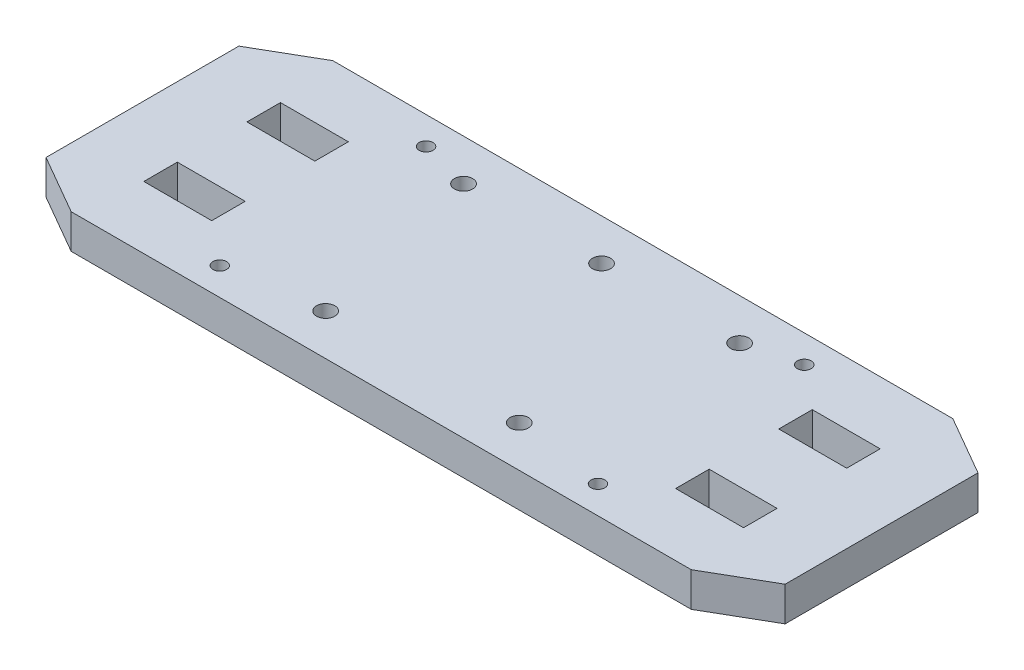
SolidWorks part; units mm, degrees
ref_plane "Front Plane" through (0, 0, 0) normal (0, 0, 1) x (1, 0, 0)
ref_plane "Top Plane" through (0, 0, 0) normal (0, 1, 0) x (1, 0, 0)
ref_plane "Right Plane" through (0, 0, 0) normal (1, 0, 0) x (0, 0, -1)
sketch "Sketch1" plane through (0, 0, 0) normal (0, 1, 0) x (1, 0, 0)
  line L0 (0, 38.05) -> (0, -38.05) construction
  line L1 (48.15, -20.05) -> (-48.15, -20.05) construction
  line L2 (48.15, -20.05) -> (48.15, 20.05) construction
  line L3 (48.15, 20.05) -> (-48.15, 20.05) construction
  line L4 (-48.15, -20.05) -> (-48.15, 20.05) construction
  line L5 (48.15, -20.05) -> (-48.15, 20.05) construction
  line L6 (48.15, 20.05) -> (-48.15, -20.05) construction
  line L7 (107.5, -38.05) -> (-107.5, -38.05)
  line L8 (107.5, -38.05) -> (107.5, 38.05)
  line L9 (107.5, 38.05) -> (-107.5, 38.05)
  line L10 (-107.5, -38.05) -> (-107.5, 38.05)
  line L11 (107.5, -38.05) -> (-107.5, 38.05) construction
  line L12 (107.5, 38.05) -> (-107.5, -38.05) construction
  circle A0 centre (-40.15, 26.05) radius 2.65
  circle A1 centre (40.15, 26.05) radius 2.65
  circle A2 centre (0, 26.05) radius 2.65
  circle A3 centre (-28.15, -26.05) radius 2.65
  circle A4 centre (28.15, -26.05) radius 2.65
  point P0 (0, 0)
  point P6 (0, 0)
  dimension "D3" = 5.3
  dimension "D1" = 96.3
  dimension "D2" = 40.1
  dimension "D4" = 6
  dimension "D5" = 8
  dimension "D6" = 6
  dimension "D7" = 20
  dimension "D8" = 215
  dimension "D9" = 12
extrude "Boss-Extrude1" add sketch "Sketch1" along normal blind 10
sketch "Sketch2" plane through (0, 10, 0) normal (0, 1, 0) x (1, 0, 0)
  line L0 (0, 0) -> (-70.9493, 0) construction
  line L1 (-87.225, -19.875) -> (-67.475, -19.875)
  line L2 (-87.225, -19.875) -> (-87.225, -10.125)
  line L3 (-87.225, -10.125) -> (-67.475, -10.125)
  line L4 (-67.475, -19.875) -> (-67.475, -10.125)
  line L5 (-87.225, -19.875) -> (-67.475, -10.125) construction
  line L6 (-87.225, -10.125) -> (-67.475, -19.875) construction
  line L7 (0, 0) -> (0, -12.151) construction
  line L8 (-87.225, 10.125) -> (-67.475, 19.875) construction
  line L9 (-87.225, 19.875) -> (-67.475, 10.125) construction
  line L10 (-67.475, 19.875) -> (-67.475, 10.125)
  line L11 (-87.225, 10.125) -> (-67.475, 10.125)
  line L12 (-87.225, 19.875) -> (-87.225, 10.125)
  line L13 (-87.225, 19.875) -> (-67.475, 19.875)
  line L14 (87.225, 19.875) -> (67.475, 10.125) construction
  line L15 (87.225, 10.125) -> (67.475, 19.875) construction
  line L16 (87.225, -10.125) -> (67.475, -19.875) construction
  line L17 (87.225, -19.875) -> (67.475, -10.125) construction
  line L18 (87.225, 19.875) -> (67.475, 19.875)
  line L19 (87.225, 19.875) -> (87.225, 10.125)
  line L20 (87.225, 10.125) -> (67.475, 10.125)
  line L21 (67.475, 19.875) -> (67.475, 10.125)
  line L22 (67.475, -19.875) -> (67.475, -10.125)
  line L23 (87.225, -10.125) -> (67.475, -10.125)
  line L24 (87.225, -19.875) -> (87.225, -10.125)
  line L25 (87.225, -19.875) -> (67.475, -19.875)
  point P0 (-77.35, -15)
  point P13 (-77.35, 15)
  point P22 (77.35, 15)
  point P23 (77.35, -15)
  dimension "D1" = 15
  dimension "D2" = 77.35
  dimension "D3" = 9.75
  dimension "D4" = 19.75
extrude "Cut-Extrude1" cut sketch "Sketch2" against normal through all
chamfer "Chamfer1" distance 10 angle 60 4 edges at (-107.5, 5, -38.05) (107.5, 5, 38.05) (107.5, 5, -38.05) (-107.5, 5, 38.05)
sketch "Sketch3" plane through (0, 10, 0) normal (0, 1, 0) x (1, 0, 0)
  line L0 (0, 0) -> (-20.2861, 0) construction
  line L1 (0, 0) -> (0, -15.5918) construction
  circle A0 centre (-55, -30) radius 2
  circle A1 centre (-55, 30) radius 2
  circle A2 centre (55, -30) radius 2
  circle A3 centre (55, 30) radius 2
  point P2 (0, 0)
  dimension "D3" = 4
  dimension "D1" = 55
  dimension "D2" = 30
extrude "Cut-Extrude2" cut sketch "Sketch3" against normal through all
